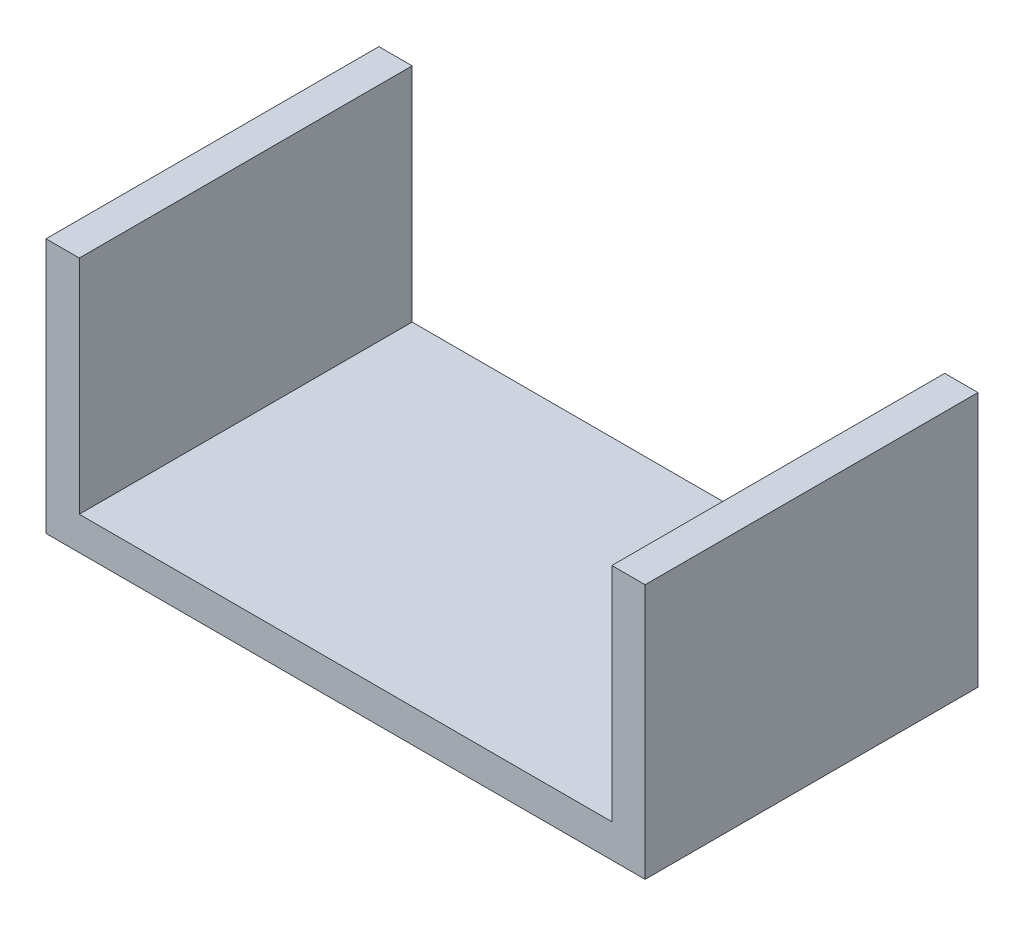
SolidWorks part; units mm, degrees
ref_plane "Front Plane" through (0, 0, 0) normal (0, 0, 1) x (1, 0, 0)
ref_plane "Top Plane" through (0, 0, 0) normal (0, 1, 0) x (1, 0, 0)
ref_plane "Right Plane" through (0, 0, 0) normal (1, 0, 0) x (0, 0, -1)
sketch "Sketch1" plane through (0, 0, 0) normal (0, 1, 0) x (1, 0, 0)
  line L1 (-27, -15) -> (27, -15)
  line L2 (-27, -15) -> (-27, 15)
  line L3 (-27, 15) -> (27, 15)
  line L4 (27, -15) -> (27, 15)
  point P4 (0, 15)
  point P6 (-27, 0)
  dimension "D1" = 54
  dimension "D2" = 30
extrude "Boss-Extrude1" add sketch "Sketch1" along normal blind 3
sketch "Sketch2" plane through (0, 3, 0) normal (0, 1, 0) x (1, 0, 0)
  line L0 (27, 15) -> (-27, 15) construction
  line L1 (-27, -15) -> (-24, -15)
  line L2 (-27, -15) -> (-27, 15)
  line L3 (-27, 15) -> (-24, 15)
  line L4 (-24, -15) -> (-24, 15)
  dimension "D1" = 3
extrude "Boss-Extrude2" add sketch "Sketch2" along normal blind 20
sketch "Sketch3" plane through (0, 3, 0) normal (0, 1, 0) x (1, 0, 0)
  line L0 (27, 15) -> (-24, 15) construction
  line L1 (27, -15) -> (24, -15)
  line L2 (27, -15) -> (27, 15)
  line L3 (27, 15) -> (24, 15)
  line L4 (24, -15) -> (24, 15)
  dimension "D1" = 3
extrude "Boss-Extrude3" add sketch "Sketch3" along normal blind 20
